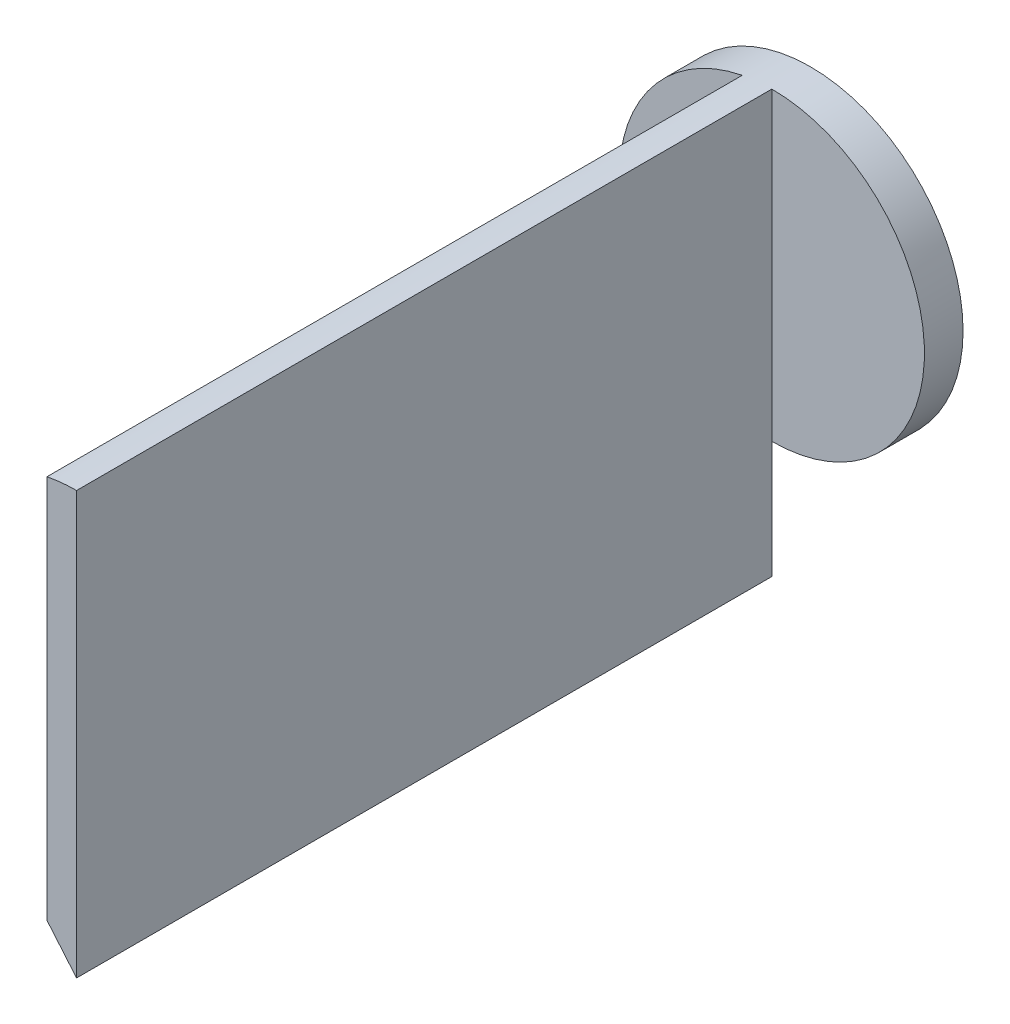
SolidWorks part; units mm, degrees
ref_plane "前视基准面" through (0, 0, 0) normal (0, 0, 1) x (1, 0, 0)
ref_plane "上视基准面" through (0, 0, 0) normal (0, 1, 0) x (1, 0, 0)
ref_plane "右视基准面" through (0, 0, 0) normal (1, 0, 0) x (0, 0, -1)
other "Configuration Table"
sketch "草图1" plane through (0, 0, 0) normal (0, 0, 1) x (1, 0, 0)
  circle A0 centre (0, 0) radius 39.5
extrude "凸台-拉伸1" add sketch "草图1" along normal blind 10
sketch "草图2" plane through (0, 0, 10) normal (0, 0, 1) x (1, 0, 0)
  line L0 (0, -69.8001) -> (0, 39.5)
  line L5 (-7.6669, 38.7488) -> (-7.6669, -60.6941)
  line L6 (-7.6669, -60.6941) -> (0, -69.8001)
  circle A3 centre (0, 0) radius 39.5 construction
  arc A4 (-7.6669, 38.7488) -> (0, 39.5) centre (0, 0) cw
  point P7 (-7.6669, -60.6941)
extrude "凸台-拉伸2" add sketch "草图2" along normal blind 180
